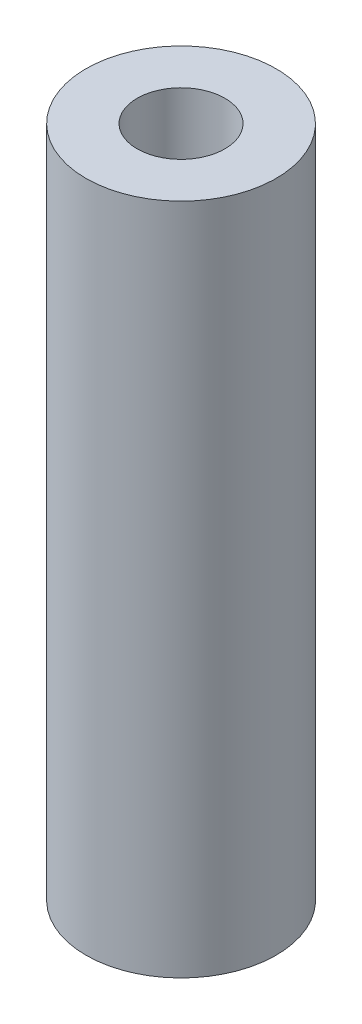
SolidWorks part; units mm, degrees
ref_plane "Plan de face" through (0, 0, 0) normal (0, 0, 1) x (1, 0, 0)
ref_plane "Plan de dessus" through (0, 0, 0) normal (0, 1, 0) x (1, 0, 0)
ref_plane "Plan de droite" through (0, 0, 0) normal (1, 0, 0) x (0, 0, -1)
sketch "Esquisse1" plane through (0, 0, 0) normal (0, 1, 0) x (1, 0, 0)
  circle A0 centre (0, 0) radius 1.5
  dimension "D1" = 3
sketch "Esquisse2" plane through (0, 0, 0) normal (0, 1, 0) x (1, 0, 0)
  circle A0 centre (0, 0) radius 3.25
  dimension "D1" = 6.5
extrude "Boss.-Extru.1" add sketch "Esquisse2" along normal blind 23
extrude "Enlèv. mat.-Extru.1" cut sketch "Esquisse1" along normal blind 28
